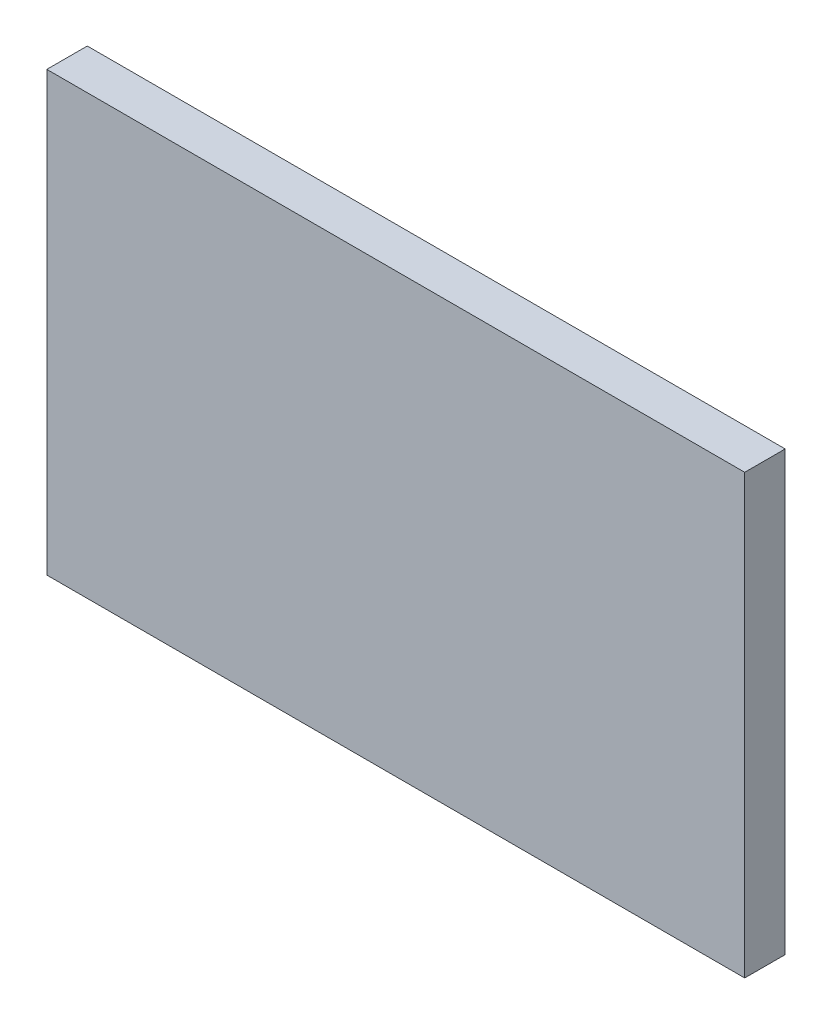
SolidWorks part; units mm, degrees
ref_plane "Plano frontal" through (0, 0, 0) normal (0, 0, 1) x (1, 0, 0)
ref_plane "Plano superior" through (0, 0, 0) normal (0, 1, 0) x (1, 0, 0)
ref_plane "Plano direito" through (0, 0, 0) normal (1, 0, 0) x (0, 0, -1)
sketch "Esboço1" plane through (0, 0, 0) normal (0, 0, 1) x (1, 0, 0)
  line L1 (-58.9151, 41.9402) -> (-41.6651, 41.9402)
  line L2 (-58.9151, 41.9402) -> (-58.9151, 31.1149)
  line L3 (-58.9151, 31.1149) -> (-41.6651, 31.1149)
  line L4 (-41.6651, 41.9402) -> (-41.6651, 31.1149)
extrude "Ressalto-extrusão1" add sketch "Esboço1" along normal blind 1
